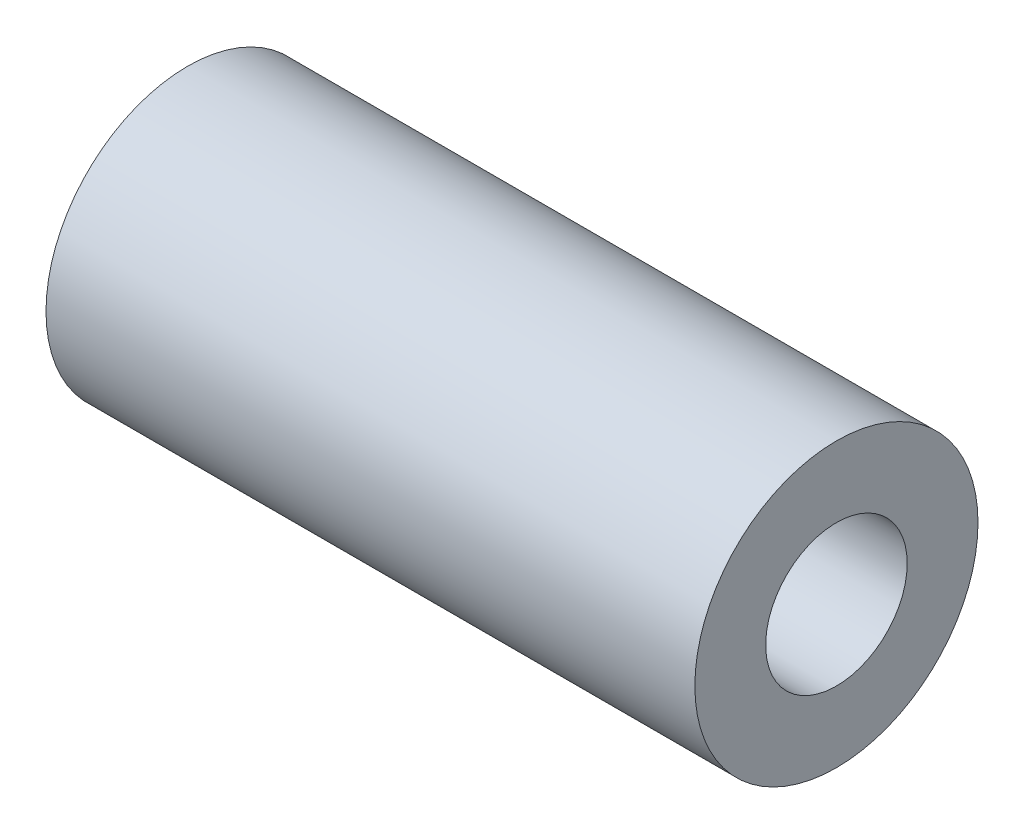
SolidWorks part; units mm, degrees
material "PLA"
ref_plane "Front Plane" through (0, 0, 0) normal (0, 0, 1) x (1, 0, 0)
ref_plane "Top Plane" through (0, 0, 0) normal (0, 1, 0) x (1, 0, 0)
ref_plane "Right Plane" through (0, 0, 0) normal (1, 0, 0) x (0, 0, -1)
sketch "Sketch1" plane through (0, 0, 0) normal (1, 0, 0) x (0, 0, -1)
  circle A0 centre (0, 0) radius 1.2
  circle A1 centre (0, 0) radius 2.4
  dimension "D1" = 4.8
  dimension "2." = 2.4
extrude "Boss-Extrude1" add sketch "Sketch1" against normal blind 11
